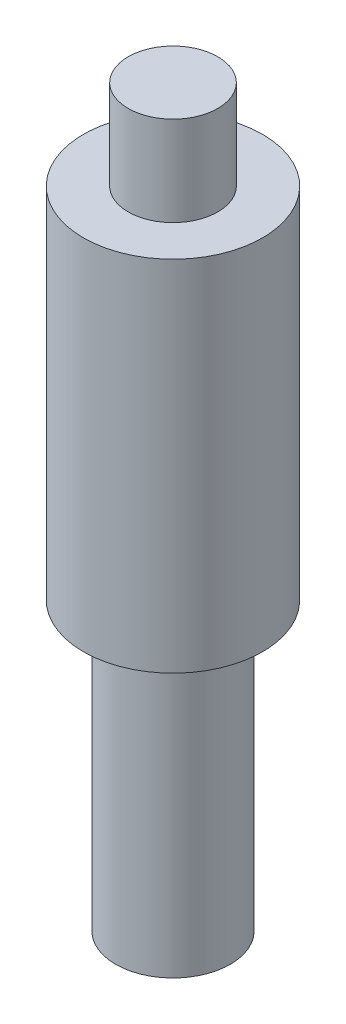
SolidWorks part; units mm, degrees
ref_plane "前视基准面" through (0, 0, 0) normal (0, 0, 1) x (1, 0, 0)
ref_plane "上视基准面" through (0, 0, 0) normal (0, 1, 0) x (1, 0, 0)
ref_plane "右视基准面" through (0, 0, 0) normal (1, 0, 0) x (0, 0, -1)
other "Configuration Table"
sketch "草图1" plane through (0, 0, 0) normal (0, 1, 0) x (1, 0, 0)
  circle A0 centre (0, 0) radius 1.6
  dimension "D1" = 3.2
extrude "凸台-拉伸1" add sketch "草图1" along normal blind 8 contours A0
sketch "草图2" plane through (0, 8, 0) normal (0, 1, 0) x (1, 0, 0)
  circle A0 centre (0, 0) radius 2.5
  dimension "D1" = 5
extrude "凸台-拉伸2" add sketch "草图2" along normal blind 10 contours A0
sketch "草图3" plane through (0, 18, 0) normal (0, 1, 0) x (1, 0, 0)
  circle A0 centre (0, 0) radius 1.25
  dimension "D1" = 2.5
extrude "凸台-拉伸3" add sketch "草图3" along normal blind 2.5
